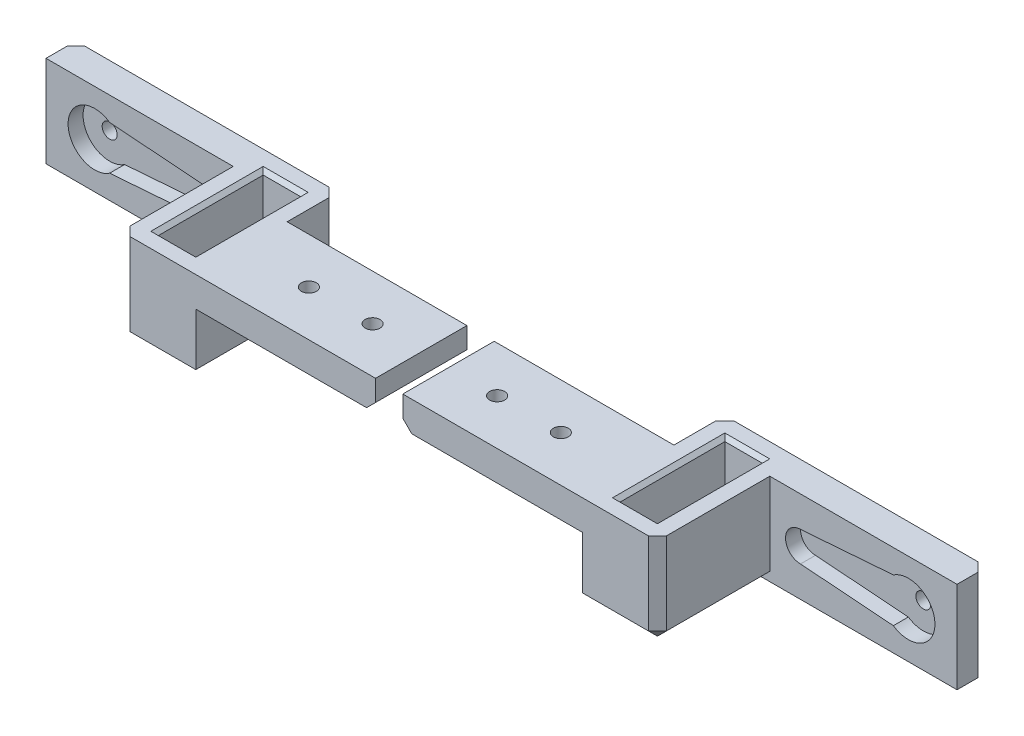
SolidWorks part; units mm, degrees
ref_plane "Front Plane" through (0, 0, 0) normal (0, 0, 1) x (1, 0, 0)
ref_plane "Top Plane" through (0, 0, 0) normal (0, 1, 0) x (1, 0, 0)
ref_plane "Right Plane" through (0, 0, 0) normal (1, 0, 0) x (0, 0, -1)
sketch "Sketch1" plane through (0, 0, 0) normal (0, 0, 1) x (1, 0, 0)
  line L1 (-35.5488, 11.7605) -> (-0.5488, 11.7605)
  line L2 (-35.5488, 11.7605) -> (-35.5488, -0.4395)
  line L3 (-35.5488, -0.4395) -> (-0.5488, -0.4395)
  line L4 (-0.5488, 11.7605) -> (-0.5488, -0.4395)
  dimension "D1" = 35
  dimension "D2" = 12.2
extrude "Boss-Extrude1" add sketch "Sketch1" along normal blind 4
sketch "Sketch2" plane through (0, 0, 4) normal (0, 0, 1) x (1, 0, 0)
  line L0 (-0.5488, 11.7605) -> (-35.5488, 11.7605) construction
  line L3 (-35.5488, 11.7605) -> (-35.5488, -0.4395) construction
  circle A0 centre (-29.0488, 5.6605) radius 1
  dimension "D1" = 2
  dimension "D2" = 6.1
  dimension "D3" = 6.5
extrude "Cut-Extrude1" cut sketch "Sketch2" against normal through all contours A0
sketch "Sketch3" plane through (0, 0, 4) normal (0, 0, 1) x (1, 0, 0)
  line L0 (-35.5488, -0.4395) -> (-0.5488, -0.4395) construction
  line L1 (-0.5488, 11.7605) -> (-10.5488, 11.7605)
  line L2 (-0.5488, 11.7605) -> (-0.5488, -0.4395)
  line L3 (-0.5488, -0.4395) -> (-10.5488, -0.4395)
  line L4 (-10.5488, 11.7605) -> (-10.5488, -0.4395)
  dimension "D1" = 10
extrude "Boss-Extrude2" add sketch "Sketch3" along normal blind 15
sketch "Sketch4" plane through (-0.5488, 0, 0) normal (1, 0, 0) x (0, 0, -1)
  line L1 (-19, 11.7605) -> (-6.8, 11.7605)
  line L2 (-19, 11.7605) -> (-19, 7.7605)
  line L3 (-19, 7.7605) -> (-6.8, 7.7605)
  line L4 (-6.8, 11.7605) -> (-6.8, 7.7605)
  dimension "D1" = 12.2
  dimension "D2" = 4
  dimension "D3" = 12.2
extrude "Boss-Extrude3" add sketch "Sketch4" along normal blind 24 contours L2 L1 L4 L3
sketch "Sketch5" plane through (0, 7.7605, 0) normal (0, -1, 0) x (1, 0, 0)
  line L0 (23.4512, 19) -> (23.4512, 6.8) construction
  line L1 (23.4512, 19) -> (-0.5488, 19) construction
  line L2 (16.9512, 12.9) -> (8.4512, 12.9) construction
  circle A0 centre (16.9512, 12.9) radius 1
  circle A1 centre (8.4512, 12.9) radius 1
  dimension "D3" = 2
  dimension "D5" = 2
  dimension "D1" = 6.5
  dimension "D2" = 6.1
  dimension "D4" = 8.5
extrude "Cut-Extrude2" cut sketch "Sketch5" against normal through all and the other way through all contours A0 | A1
sketch "Sketch7" plane through (0, 0, 0) normal (0, 0, -1) x (-1, 0, 0)
  line L0 (0.5488, 11.7605) -> (35.5488, 11.7605) construction
  line L1 (23.0488, 5.6605) -> (19.2988, 7.8256)
  line L2 (19.2988, 7.8256) -> (19.2988, 3.4954)
  line L3 (19.2988, 3.4954) -> (23.0488, 5.6605)
  line L5 (35.5488, 11.7605) -> (35.5488, -0.4395) construction
  circle A0 centre (20.5488, 5.6605) radius 1.25 construction
  dimension "D2" = 2.5
  dimension "D1" = 6.1
  dimension "D3" = 15
  dimension "D4" = 3.75
extrude "Cut-Extrude3" cut sketch "Sketch7" against normal blind 0.5
chamfer "Chamfer1" distance 1.2 angle 45 8 edges at (23.4512, 7.7605, 12.9) (-35.5488, 5.6605, 0) (-0.5488, 5.6605, 0) (-10.5488, -0.4395, 11.5) (-5.5488, -0.4395, 19) (-10.5488, 5.6605, 19) (-18.0488, -0.4395, 0) (-0.5488, -0.4395, 9.5)
sketch "Sketch24" plane through (0, 0, 4) normal (0, 0, 1) x (1, 0, 0)
  line L0 (-29.0488, 5.6605) -> (-14.6488, 5.6605) construction
  line L1 (-29.0488, 5.6605) -> (-26.6857, 5.6605) construction
  line L6 (-29.0488, 5.6605) -> (-27.0488, 5.6605) construction
  line L8 (-27.0488, 2.7275) -> (-14.6488, 3.6605)
  line L10 (-14.6488, 7.6605) -> (-27.0488, 8.5935)
  arc A0 (-27.0488, 8.5935) -> (-27.0488, 2.7275) centre (-29.0488, 5.6605) ccw
  arc A1 (-14.6488, 3.6605) -> (-14.6488, 7.6605) centre (-14.6488, 5.6605) ccw
  dimension "D1" = 7.1
  dimension "D2" = 4
  dimension "D3" = 14.4
  dimension "D4" = 12.4
  dimension "D5" = 12.4
extrude "Cut-Extrude17" cut sketch "Sketch24" against normal blind 2
sketch "Sketch25" plane through (0, 7.7605, 0) normal (0, -1, 0) x (1, 0, 0)
  line L0 (16.9512, 12.9) -> (2.5512, 12.9) construction
  line L1 (16.9512, 12.9) -> (14.5882, 12.9) construction
  line L6 (16.9512, 12.9) -> (14.9512, 12.9) construction
  line L7 (2.5512, 14.9) -> (14.9512, 15.833)
  line L9 (14.9512, 9.967) -> (2.5512, 10.9)
  arc A0 (14.9512, 9.967) -> (14.9512, 15.833) centre (16.9512, 12.9) ccw
  arc A1 (2.5512, 14.9) -> (2.5512, 10.9) centre (2.5512, 12.9) ccw
  dimension "D1" = 7.1
  dimension "D2" = 4
  dimension "D3" = 14.4
  dimension "D4" = 12.4
  dimension "D5" = 12.4
extrude "Cut-Extrude18" cut sketch "Sketch25" against normal blind 2
sketch "Sketch26" plane through (0, 11.7605, 0) normal (0, 1, 0) x (1, 0, 0)
  line L0 (-1.7488, 0) -> (-34.3488, 0) construction
  line L1 (-8.0488, -2.5) -> (-3.0488, -2.5)
  line L2 (-8.0488, -2.5) -> (-8.0488, -16.5)
  line L3 (-8.0488, -16.5) -> (-3.0488, -16.5)
  line L4 (-3.0488, -2.5) -> (-3.0488, -16.5)
  line L5 (-10.5488, -17.8) -> (-10.5488, -4) construction
  line L6 (-0.5488, -6.8) -> (-0.5488, -1.2) construction
  line L7 (23.4512, -19) -> (-9.3488, -19) construction
  dimension "D1" = 2.5
  dimension "D2" = 2.5
  dimension "D3" = 2.5
  dimension "D4" = 2.5
extrude "Cut-Extrude19" cut sketch "Sketch26" against normal through all
chamfer "Chamfer2" distance 0.5 angle 45 8 edges at (-3.0488, -0.4395, 9.5) (-5.5488, -0.4395, 2.5) (-8.0488, -0.4395, 9.5) (-5.5488, -0.4395, 16.5) (-3.0488, 11.7605, 9.5) (-5.5488, 11.7605, 2.5) (-5.5488, 11.7605, 16.5) (-8.0488, 11.7605, 9.5)
sketch "Sketch27" plane through (0, 0, 0) normal (0, 0, 1) x (1, 0, 0)
  line L0 (25.2709, 14.1875) -> (25.2709, -3.4963) construction
ref_plane "Plane1" through (25.2709, 0, 0) normal (-1, 0, 0) x (0, -1, 0)
mirror "Mirror1" about plane through (25.2709, 0, 0) normal (-1, 0, 0) of bodies 124
split "Split1" trim tools "Plane1" bodies to split 124 125 resulting bodies 126 127
